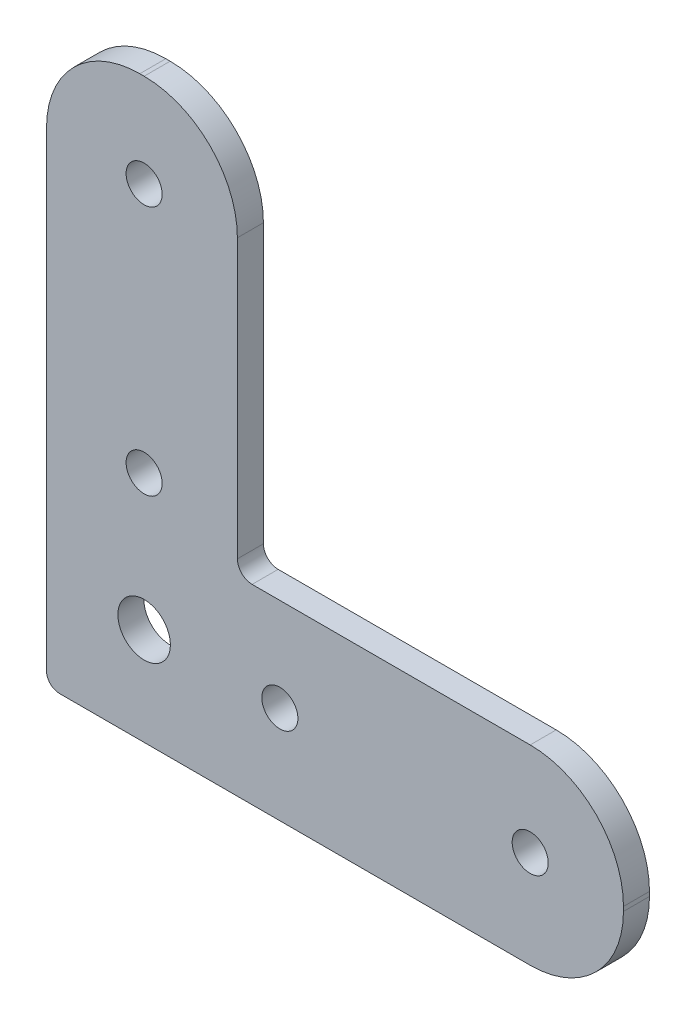
SolidWorks part; units mm, degrees
material "PET"
ref_plane "Front Plane" through (0, 0, 0) normal (0, 0, 1) x (1, 0, 0)
ref_plane "Top Plane" through (0, 0, 0) normal (0, 1, 0) x (1, 0, 0)
ref_plane "Right Plane" through (0, 0, 0) normal (1, 0, 0) x (0, 0, -1)
sketch "Sketch1" plane through (0, 0, 0) normal (0, 0, 1) x (1, 0, 0)
  line L0 (0, 0) -> (0, 133)
  line L1 (22.5, 22.5) -> (67, 22.5) construction
  line L2 (67, 22.5) -> (111.5, 22.5) construction
  line L3 (22.5, 22.5) -> (22.5, 53.7884) construction
  line L4 (45, 133) -> (0, 133)
  line L5 (133, 0) -> (0, 0)
  line L6 (22.5, 53.7884) -> (22.5, 85.0768) construction
  line L7 (133, 45) -> (133, 0)
  line L9 (133, 22.5) -> (111.5, 22.5) construction
  line L10 (22.5, 133) -> (22.5, 85.0768) construction
  line L11 (44, 133) -> (44, 44)
  line L12 (44, 44) -> (133, 44)
  circle A0 centre (22.5, 22.5) radius 6.05 construction
  circle A1 centre (22.5, 111.5) radius 4.1187 construction
  circle A2 centre (111.5, 22.5) radius 4.1188 construction
  circle A3 centre (22.5, 53.7884) radius 4.1188 construction
  circle A4 centre (53.7884, 22.5) radius 4.1188 construction
  dimension "D1" = 21.5
  dimension "D2" = 22.5
  dimension "D7" = 8.2375
  dimension "D8" = 12.1
  dimension "C" = 133
  dimension "D3" = 31.2884
  dimension "B" = 133
  dimension "D4" = 22.5
  dimension "D5" = 21.5
  dimension "D6" = 21.5
  dimension "D9" = 31.2884
extrude "Boss-Extrude1" add sketch "Sketch1" along normal mid plane 6 contours L12 L11 L4 L0 L5 L7 A3 A2 A1 A0
fillet "Fillet4" radius 21.5 4 edges at (133, 44, 0) (133, 0, 0) (44, 133, 0) (0, 133, 0)
fillet "Fillet5" radius 3.4 1 edges at (44, 44, 0)
fillet "Fillet6" radius 3 1 edges at (0, 0, 0)
hole_wizard "5/16 Clearance Hole1" positions "Sketch4" profile "Sketch3" hole size "5/16" standard "ANSI Inch" end condition through all
sketch "Sketch4" plane through (0, 0, 3) normal (0, 0, 1) x (1, 0, 0)
  point P0 (22.5, 111.5)
  point P3 (22.5, 53.7884)
  point P6 (53.7884, 22.5)
  point P9 (111.5, 22.5)
sketch "Sketch3" plane through (22.5, 111.5, 3) normal (1, 0, 0) x (0, -1, 0)
  line L0 (0, 0) -> (0, 6)
  line L1 (0, 6) -> (4.1592, 6)
  line L2 (4.1592, 6) -> (4.1592, 0)
  line L5 (4.1592, 0) -> (0, 0)
  line L11 (0, -6.35) -> (0, 107.95) construction
  dimension "Thru Hole Dia." = 8.3185
  dimension "Thru Hole Depth" = 6
hole_wizard "M12 Clearance Hole1" positions "Sketch7" profile "Sketch6" hole size "M12" standard "ANSI Metric" end condition through all
sketch "Sketch7" plane through (0, 0, 3) normal (0, 0, 1) x (1, 0, 0)
  point P0 (22.5, 22.5)
sketch "Sketch6" plane through (22.5, 22.5, 3) normal (1, 0, 0) x (0, -1, 0)
  line L0 (0, 0) -> (0, 6)
  line L1 (0, 6) -> (6.05, 6)
  line L2 (6.05, 6) -> (6.05, 0)
  line L5 (6.05, 0) -> (0, 0)
  line L11 (0, -6.35) -> (0, 107.95) construction
  dimension "Thru Hole Dia." = 12.1
  dimension "Thru Hole Depth" = 6
